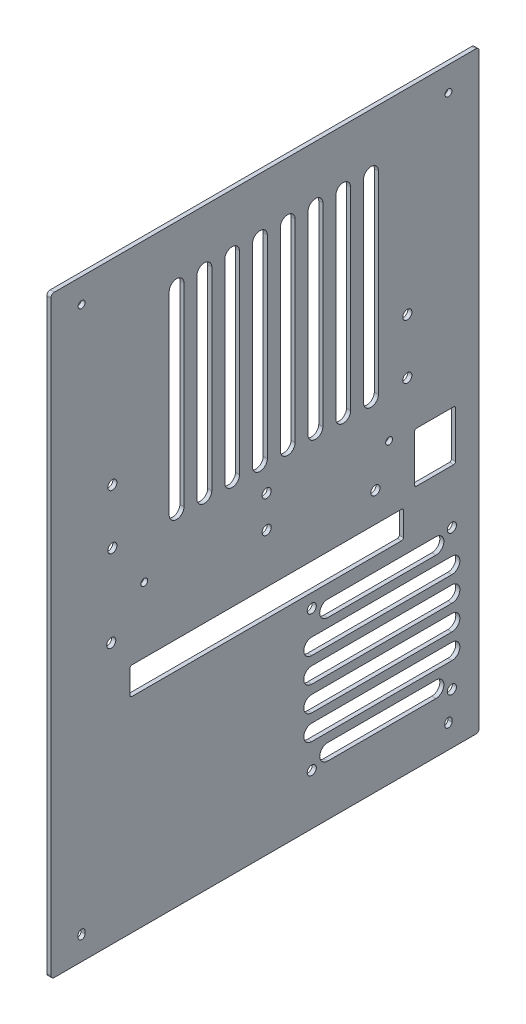
SolidWorks part; units mm, degrees
ref_plane "前视基准面" through (0, 0, 0) normal (0, 0, 1) x (1, 0, 0)
ref_plane "上视基准面" through (0, 0, 0) normal (0, 1, 0) x (1, 0, 0)
ref_plane "右视基准面" through (0, 0, 0) normal (1, 0, 0) x (0, 0, -1)
sketch "草图1" plane through (0, 0, 0) normal (1, 0, 0) x (0, 0, -1)
  line L1 (0, 0) -> (188, 0)
  line L2 (0, 0) -> (0, 260.5)
  line L3 (0, 260.5) -> (188, 260.5)
  line L4 (188, 0) -> (188, 260.5)
  circle A0 centre (174.5, 249.8) radius 1.525 construction
  circle A1 centre (174.5, 10.4) radius 1.525 construction
  circle A2 centre (13.5, 249.8) radius 1.525 construction
  circle A3 centre (13.5, 10.4) radius 1.525 construction
  dimension "D7" = 3.05
  dimension "D1" = 260.5
  dimension "D2" = 188
  dimension "D3" = 13.5
  dimension "D4" = 10.7
  dimension "D5" = 239.4
  dimension "D6" = 13.5
extrude "base" add sketch "草图1" along normal blind 1.8
sketch "草图3" plane through (1.8, 0, 0) normal (1, 0, 0) x (0, 0, -1)
  line L0 (188, 0) -> (188, 260.5) construction
  line L1 (0, 95.8) -> (188, 95.8) construction
  line L2 (188, 260.5) -> (0, 260.5) construction
  line L4 (0, 260.5) -> (0, 0) construction
  line L5 (34.725, 89.8) -> (154.725, 89.8)
  line L6 (34.725, 89.8) -> (34.725, 101.8)
  line L7 (34.725, 101.8) -> (154.725, 101.8)
  line L8 (154.725, 89.8) -> (154.725, 101.8)
  line L9 (13.5, 10.9) -> (13.5, 9.9) construction
  line L10 (15.025, 10.9) -> (15.025, 9.9)
  line L11 (11.975, 10.9) -> (11.975, 9.9)
  line L12 (174.5, 10.9) -> (174.5, 9.9) construction
  line L13 (176.025, 10.9) -> (176.025, 9.9)
  line L14 (172.975, 10.9) -> (172.975, 9.9)
  line L15 (0, 0) -> (188, 0) construction
  line L16 (41, 130.5) -> (148.45, 130.5) construction
  line L17 (94.725, 137.5) -> (94.725, 130.5) construction
  circle A0 centre (13.5, 249.8) radius 1.525
  circle A1 centre (174.5, 249.8) radius 1.525
  circle A2 centre (13.5, 10.4) radius 1.525 construction
  circle A3 centre (174.5, 10.4) radius 1.525 construction
  circle A4 centre (156.45, 150.5) radius 2
  circle A5 centre (41, 130.5) radius 1.5
  circle A6 centre (148.45, 130.5) radius 1.5
  circle A7 centre (27, 150.5) radius 2
  circle A8 centre (26.5, 114.7) radius 2
  circle A9 centre (142.45, 114.7) radius 2
  circle A10 centre (27, 174.5) radius 2
  circle A11 centre (156.45, 174.5) radius 2
  arc A12 (15.025, 10.9) -> (11.975, 10.9) centre (13.5, 10.9) ccw
  arc A13 (11.975, 9.9) -> (15.025, 9.9) centre (13.5, 9.9) ccw
  arc A14 (176.025, 10.9) -> (172.975, 10.9) centre (174.5, 10.9) ccw
  arc A15 (172.975, 9.9) -> (176.025, 9.9) centre (174.5, 9.9) ccw
  circle A16 centre (94.725, 137.5) radius 2
  circle A17 centre (94.725, 123.5) radius 2
  point P26 (34.725, 95.8)
  point P39 (13.5, 10.4)
  point P48 (174.5, 10.4)
  dimension "D5" = 3.05
  dimension "D8" = 4
  dimension "D24" = 3
  dimension "D27" = 3.05
  dimension "D29" = 7
  dimension "D1" = 13.5
  dimension "D2" = 10.7
  dimension "D3" = 239.4
  dimension "D4" = 13.5
  dimension "D6" = 130
  dimension "D7" = 41
  dimension "D9" = 107.45
  dimension "D10" = 120
  dimension "D11" = 154
  dimension "D12" = 6.275
  dimension "D13" = 6.275
  dimension "D14" = 12
  dimension "D15" = 154
  dimension "D16" = 6
  dimension "D17" = 14.5
  dimension "D18" = 20
  dimension "D19" = 8
  dimension "D20" = 14
  dimension "D21" = 15.8
  dimension "D22" = 24
  dimension "D23" = 24
  dimension "D25" = 1
  dimension "D26" = 1
  dimension "D28" = 10.4
extrude "固定孔+pcie排线孔+加固板" cut sketch "草图3" against normal up to surface (1.8 mm away) up to face at (0, 130.25, -94)
sketch "草图5" plane through (1.8, 0, 0) normal (1, 0, 0) x (0, 0, -1)
  line L0 (180, 0) -> (180, 260.5) construction
  line L1 (159.6, 129.3) -> (177.6, 129.3)
  line L2 (159.6, 129.3) -> (159.6, 107.3)
  line L3 (159.6, 107.3) -> (177.6, 107.3)
  line L4 (177.6, 129.3) -> (177.6, 107.3)
  line L5 (0, 0) -> (188, 0) construction
  line L6 (188, 260.5) -> (0, 260.5) construction
  line L7 (188, 0) -> (188, 260.5) construction
  line L10 (154.725, 101.8) -> (34.725, 101.8) construction
  dimension "D1" = 18
  dimension "D2" = 22
  dimension "D3" = 8
  dimension "D4" = 2.4
  dimension "D5" = 5.5
extrude "电源孔" cut sketch "草图5" against normal up to next
sketch "草图4" plane through (1.8, 0, 0) normal (1, 0, 0) x (0, 0, -1)
  line L0 (0, 8) -> (188, 8) construction
  line L1 (0, 260.5) -> (0, 0) construction
  line L2 (188, 0) -> (188, 260.5) construction
  line L4 (110, 88.3) -> (180.5, 88.3) construction
  line L5 (180.5, 88.3) -> (180.5, 17.8) construction
  line L6 (180.5, 17.8) -> (110, 17.8) construction
  line L7 (110, 17.8) -> (110, 88.3) construction
  line L8 (114.5, 83.8) -> (176, 83.8) construction
  line L9 (114.5, 83.8) -> (114.5, 22.3) construction
  line L10 (114.5, 53.05) -> (110, 53.05) construction
  line L11 (145.25, 83.8) -> (145.25, 88.3) construction
  line L14 (188, 0) -> (188, 260.5) construction
  line L15 (0, 0) -> (188, 0) construction
  line L16 (34.725, 89.8) -> (154.725, 89.8) construction
  circle A0 centre (114.5, 83.8) radius 2
  circle A1 centre (176, 83.8) radius 2
  circle A2 centre (176, 22.3) radius 2
  circle A3 centre (114.5, 22.3) radius 2
  dimension "D1" = 4
  dimension "D3" = 70.5
  dimension "D5" = 6
  dimension "D2" = 61.5
  dimension "D4" = 8
  dimension "D6" = 12
extrude "辅助扇" cut sketch "草图4" against normal up to next contours A0 | A1 | A3 | A2
sketch "草图2" plane through (1.8, 0, 0) normal (1, 0, 0) x (0, 0, -1)
  line L0 (55.1875, 235.5) -> (55.1875, 150.5) construction
  line L1 (58.4375, 235.5) -> (58.4375, 150.5)
  line L2 (51.9375, 235.5) -> (51.9375, 150.5)
  line L3 (67.375, 235.5) -> (67.375, 150.5) construction
  line L4 (70.625, 235.5) -> (70.625, 150.5)
  line L5 (64.125, 235.5) -> (64.125, 150.5)
  line L6 (79.5625, 235.5) -> (79.5625, 150.5) construction
  line L7 (82.8125, 235.5) -> (82.8125, 150.5)
  line L8 (76.3125, 235.5) -> (76.3125, 150.5)
  line L9 (91.75, 235.5) -> (91.75, 150.5) construction
  line L10 (95, 235.5) -> (95, 150.5)
  line L11 (88.5, 235.5) -> (88.5, 150.5)
  line L12 (103.9375, 235.5) -> (103.9375, 150.5) construction
  line L13 (107.1875, 235.5) -> (107.1875, 150.5)
  line L14 (100.6875, 235.5) -> (100.6875, 150.5)
  line L15 (116.125, 235.5) -> (116.125, 150.5) construction
  line L16 (119.375, 235.5) -> (119.375, 150.5)
  line L17 (112.875, 235.5) -> (112.875, 150.5)
  line L18 (128.3125, 235.5) -> (128.3125, 150.5) construction
  line L19 (131.5625, 235.5) -> (131.5625, 150.5)
  line L20 (125.0625, 235.5) -> (125.0625, 150.5)
  line L21 (140.5, 235.5) -> (140.5, 150.5) construction
  line L22 (143.75, 235.5) -> (143.75, 150.5)
  line L23 (137.25, 235.5) -> (137.25, 150.5)
  line L24 (188, 0) -> (188, 260.5) construction
  line L27 (188, 260.5) -> (0, 260.5) construction
  line L28 (0, 260.5) -> (0, 0) construction
  line L29 (121.5, 80.3) -> (169, 80.3) construction
  line L30 (121.5, 83.8) -> (169, 83.8)
  line L31 (121.5, 76.8) -> (169, 76.8)
  line L32 (121.5, 69.4) -> (169, 69.4) construction
  line L33 (121.5, 72.9) -> (169, 72.9) construction
  line L34 (121.5, 65.9) -> (169, 65.9) construction
  line L35 (121.5, 58.5) -> (169, 58.5) construction
  line L36 (121.5, 62) -> (169, 62) construction
  line L37 (121.5, 55) -> (169, 55) construction
  line L38 (121.5, 47.6) -> (169, 47.6) construction
  line L39 (121.5, 51.1) -> (169, 51.1) construction
  line L40 (121.5, 44.1) -> (169, 44.1) construction
  line L41 (121.5, 36.7) -> (169, 36.7) construction
  line L42 (121.5, 40.2) -> (169, 40.2) construction
  line L43 (121.5, 33.2) -> (169, 33.2) construction
  line L44 (121.5, 80.3) -> (121.5, 69.4) construction
  line L45 (188, 0) -> (188, 260.5) construction
  line L46 (121.5, 25.8) -> (169, 25.8) construction
  line L47 (0, 125.5) -> (188, 125.5) construction
  line L48 (121.5, 29.3) -> (169, 29.3)
  line L49 (121.5, 22.3) -> (169, 22.3)
  line L53 (169, 80.3) -> (176, 80.3) construction
  line L56 (176, 80.3) -> (176, 83.8) construction
  line L57 (114.5, 83.8) -> (114.5, 80.3) construction
  line L58 (114.5, 80.3) -> (121.5, 80.3) construction
  line L59 (121.5, 25.8) -> (114.5, 25.8) construction
  line L60 (114.5, 25.8) -> (114.5, 22.3) construction
  line L61 (114.5, 69.4) -> (176, 69.4) construction
  line L64 (114.5, 72.9) -> (176, 72.9)
  line L65 (114.5, 65.9) -> (176, 65.9)
  line L66 (114.5, 58.5) -> (176, 58.5) construction
  line L67 (114.5, 62) -> (176, 62)
  line L68 (114.5, 55) -> (176, 55)
  line L69 (114.5, 47.6) -> (176, 47.6) construction
  line L70 (114.5, 51.1) -> (176, 51.1)
  line L71 (114.5, 44.1) -> (176, 44.1)
  line L72 (114.5, 36.7) -> (176, 36.7) construction
  line L73 (114.5, 40.2) -> (176, 40.2)
  line L74 (114.5, 33.2) -> (176, 33.2)
  arc A0 (58.4375, 235.5) -> (51.9375, 235.5) centre (55.1875, 235.5) ccw
  arc A1 (51.9375, 150.5) -> (58.4375, 150.5) centre (55.1875, 150.5) ccw
  arc A2 (70.625, 235.5) -> (64.125, 235.5) centre (67.375, 235.5) ccw
  arc A3 (64.125, 150.5) -> (70.625, 150.5) centre (67.375, 150.5) ccw
  arc A4 (82.8125, 235.5) -> (76.3125, 235.5) centre (79.5625, 235.5) ccw
  arc A5 (76.3125, 150.5) -> (82.8125, 150.5) centre (79.5625, 150.5) ccw
  arc A6 (95, 235.5) -> (88.5, 235.5) centre (91.75, 235.5) ccw
  arc A7 (88.5, 150.5) -> (95, 150.5) centre (91.75, 150.5) ccw
  arc A8 (107.1875, 235.5) -> (100.6875, 235.5) centre (103.9375, 235.5) ccw
  arc A9 (100.6875, 150.5) -> (107.1875, 150.5) centre (103.9375, 150.5) ccw
  arc A10 (119.375, 235.5) -> (112.875, 235.5) centre (116.125, 235.5) ccw
  arc A11 (112.875, 150.5) -> (119.375, 150.5) centre (116.125, 150.5) ccw
  arc A12 (131.5625, 235.5) -> (125.0625, 235.5) centre (128.3125, 235.5) ccw
  arc A13 (125.0625, 150.5) -> (131.5625, 150.5) centre (128.3125, 150.5) ccw
  arc A14 (143.75, 235.5) -> (137.25, 235.5) centre (140.5, 235.5) ccw
  arc A15 (137.25, 150.5) -> (143.75, 150.5) centre (140.5, 150.5) ccw
  arc A18 (121.5, 83.8) -> (121.5, 76.8) centre (121.5, 80.3) ccw
  arc A19 (169, 76.8) -> (169, 83.8) centre (169, 80.3) ccw
  arc A20 (121.5, 72.9) -> (121.5, 65.9) centre (121.5, 69.4) ccw construction
  arc A21 (169, 65.9) -> (169, 72.9) centre (169, 69.4) ccw construction
  arc A22 (121.5, 62) -> (121.5, 55) centre (121.5, 58.5) ccw construction
  arc A23 (169, 55) -> (169, 62) centre (169, 58.5) ccw construction
  arc A24 (121.5, 51.1) -> (121.5, 44.1) centre (121.5, 47.6) ccw construction
  arc A25 (169, 44.1) -> (169, 51.1) centre (169, 47.6) ccw construction
  arc A26 (121.5, 40.2) -> (121.5, 33.2) centre (121.5, 36.7) ccw construction
  arc A27 (169, 33.2) -> (169, 40.2) centre (169, 36.7) ccw construction
  arc A29 (121.5, 29.3) -> (121.5, 22.3) centre (121.5, 25.8) ccw
  arc A30 (169, 22.3) -> (169, 29.3) centre (169, 25.8) ccw
  arc A33 (114.5, 72.9) -> (114.5, 65.9) centre (114.5, 69.4) ccw
  arc A34 (176, 65.9) -> (176, 72.9) centre (176, 69.4) ccw
  arc A35 (114.5, 62) -> (114.5, 55) centre (114.5, 58.5) ccw
  arc A36 (176, 55) -> (176, 62) centre (176, 58.5) ccw
  arc A37 (114.5, 51.1) -> (114.5, 44.1) centre (114.5, 47.6) ccw
  arc A38 (176, 44.1) -> (176, 51.1) centre (176, 47.6) ccw
  arc A39 (114.5, 40.2) -> (114.5, 33.2) centre (114.5, 36.7) ccw
  arc A40 (176, 33.2) -> (176, 40.2) centre (176, 36.7) ccw
  point P2 (55.1875, 193)
  point P11 (67.375, 193)
  point P18 (79.5625, 193)
  point P25 (91.75, 193)
  point P32 (103.9375, 193)
  point P39 (116.125, 193)
  point P46 (128.3125, 193)
  point P53 (140.5, 193)
  point P62 (145.25, 69.4)
  point P69 (145.25, 80.3)
  point P78 (145.25, 69.4)
  point P85 (145.25, 58.5)
  point P92 (145.25, 47.6)
  point P99 (145.25, 36.7)
  point P112 (145.25, 25.8)
  point P129 (145.25, 58.5)
  point P137 (145.25, 47.6)
  point P146 (145.25, 36.7)
  dimension "D11" = 3.25
  dimension "D12" = 4
  dimension "D8" = 7
  dimension "D10" = 3.5
  dimension "D2" = 85
  dimension "D4" = 12.1875
  dimension "D5" = 25
  dimension "D6" = 47.5
  dimension "D7" = 3.5
  dimension "D13" = 110
  dimension "D3" = 8
  dimension "D9" = 6
extrude "ther" cut sketch "草图2" along direction (-1, 0, 0) on the side against the normal up to next (1.8 mm away)
fillet "圆角1" radius 1.5 4 edges at (0.9, 0, -188) (0.9, 0, 0) (0.9, 260.5, 0) (0.9, 260.5, -188)
fillet "圆角2" radius 0.8 8 edges at (0.9, 101.8, -154.725) (0.9, 89.8, -154.725) (0.9, 89.8, -34.725) (0.9, 101.8, -34.725) (0.9, 107.3, -177.6) (0.9, 129.3, -177.6) (0.9, 129.3, -159.6) (0.9, 107.3, -159.6)
